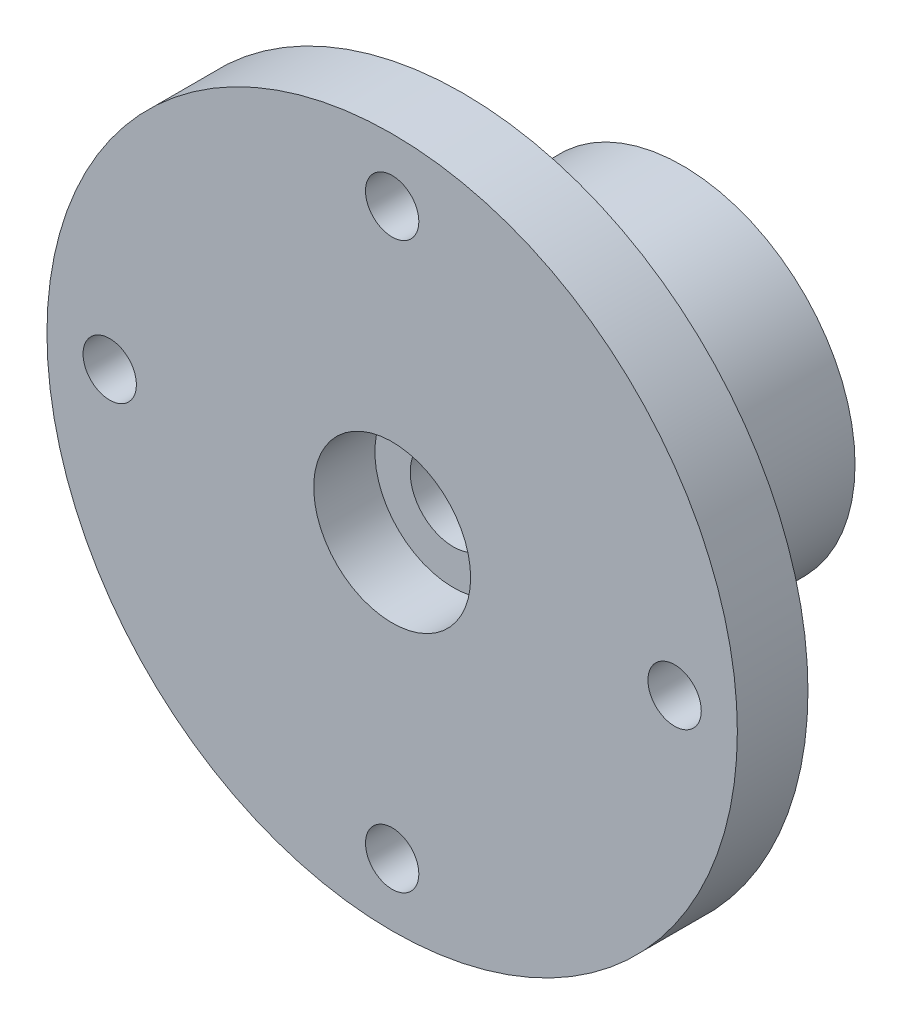
SolidWorks part; units mm, degrees
material "6061-T6 (SS)"
ref_plane "Front Plane" through (0, 0, 0) normal (0, 0, 1) x (1, 0, 0)
ref_plane "Top Plane" through (0, 0, 0) normal (0, 1, 0) x (1, 0, 0)
ref_plane "Right Plane" through (0, 0, 0) normal (1, 0, 0) x (0, 0, -1)
sketch "Sketch1" plane through (0, 0, 0) normal (0, 0, 1) x (1, 0, 0)
  circle A0 centre (0, 0) radius 11
  dimension "D1" = 22
extrude "Boss-Extrude1" add sketch "Sketch1" along normal blind 14
sketch "Sketch2" plane through (0, 0, 14) normal (0, 0, 1) x (1, 0, 0)
  circle A0 centre (0, 0) radius 22
  dimension "D1" = 44
extrude "Boss-Extrude2" add sketch "Sketch2" along normal blind 4.5
sketch "Sketch3" plane through (0, 0, 18.5) normal (0, 0, 1) x (1, 0, 0)
  circle A0 centre (0, 0) radius 18 construction
  point P4 (0, 18)
  point P9 (18, 0)
  point P10 (0, -18)
  point P11 (-18, 0)
  dimension "D1" = 36
  dimension "D2" = 4
hole_wizard "M3 Clearance Hole1" positions "Sketch3" profile "Sketch4" hole size "M3" standard "DIN" end condition through all
sketch "Sketch4" plane through (-18, 0, 18.5) normal (1, 0, 0) x (0, -1, 0)
  line L0 (0, 0) -> (0, 18.5)
  line L1 (0, 18.5) -> (1.7, 18.5)
  line L2 (1.7, 18.5) -> (1.7, 0)
  line L5 (1.7, 0) -> (0, 0)
  line L11 (0, -6.35) -> (0, 107.95) construction
  dimension "Thru Hole Dia." = 3.4
  dimension "Thru Hole Depth" = 18.5
sketch "Sketch5" plane through (0, 0, 18.5) normal (0, 0, 1) x (1, 0, 0)
  point P0 (0, 0)
hole_wizard "CBORE for M5 Hex Socket Thin Head Cap Screw1" positions "Sketch5" profile "Sketch6" counterbore size "M5" standard "DIN" end condition through all
sketch "Sketch6" plane through (0, 0, 18.5) normal (1, 0, 0) x (0, -1, 0)
  line L0 (0, 0) -> (0, 18.5)
  line L1 (0, 18.5) -> (2.75, 18.5)
  line L3 (2.75, 18.5) -> (2.75, 3.9)
  line L4 (2.75, 3.9) -> (5, 3.9)
  line L5 (5, 3.9) -> (5, 0)
  line L7 (5, 0) -> (0, 0)
  line L11 (0, -6.35) -> (0, 107.95) construction
  dimension "Thru Hole Dia." = 5.5
  dimension "Thru Hole Depth" = 18.5
  dimension "C'Bore Dia." = 10
  dimension "C'Bore Depth" = 3.9
fillet "Fillet1" radius 0.5 1 edges at (11, 0, 14)
